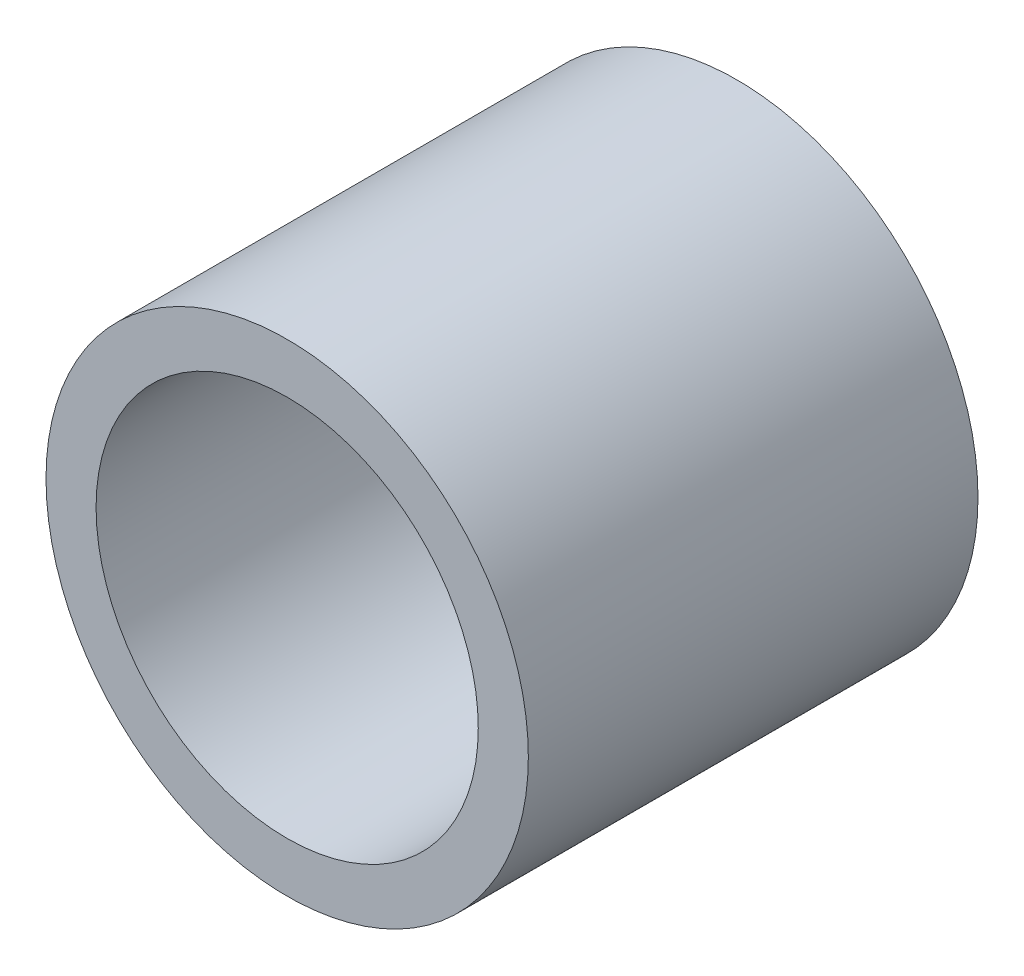
SolidWorks part; units mm, degrees
ref_plane "Front Plane" through (0, 0, 0) normal (0, 0, 1) x (1, 0, 0)
ref_plane "Top Plane" through (0, 0, 0) normal (0, 1, 0) x (1, 0, 0)
ref_plane "Right Plane" through (0, 0, 0) normal (1, 0, 0) x (0, 0, -1)
sketch "Sketch1" plane through (0, 0, 0) normal (0, 0, 1) x (1, 0, 0)
  circle A0 centre (0, 0) radius 14.986
  dimension "D1" = 29.972
extrude "Boss-Extrude1" add sketch "Sketch1" along normal blind 30.988
sketch "Sketch2" plane through (0, 0, 30.988) normal (0, 0, 1) x (1, 0, 0)
  circle A0 centre (0, 0) radius 11.8745
  dimension "D1" = 23.749
extrude "Cut-Extrude1" cut sketch "Sketch2" against normal blind 29.0322
sketch "Sketch3" plane through (0, 0, 30.988) normal (0, 0, 1) x (1, 0, 0)
  circle A0 centre (0, 0) radius 14.986
  circle A1 centre (0, 0) radius 11.8745
  circle A2 centre (0, 0) radius 11.8745 construction
  circle A3 centre (0, 0) radius 14.986 construction
extrude "Cut-Extrude2" cut sketch "Sketch3" against normal blind 3.048
